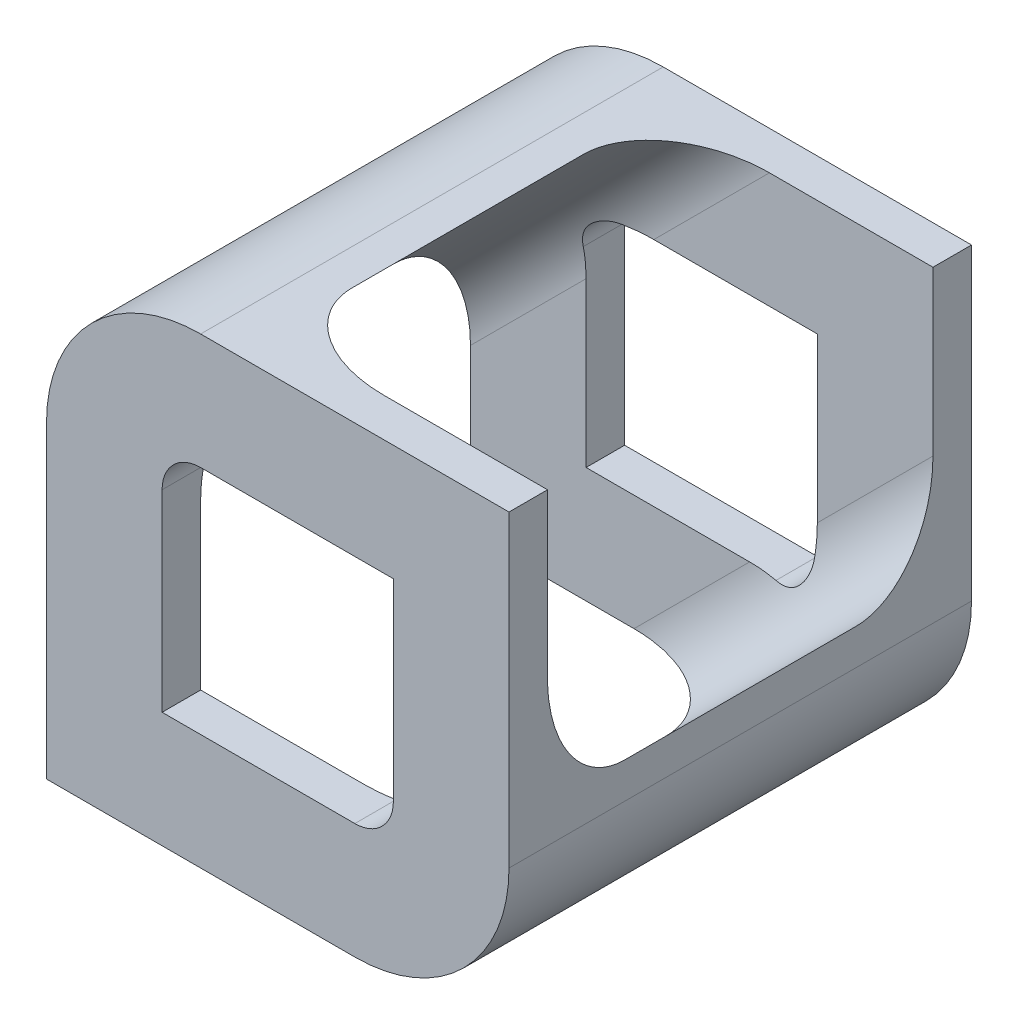
SolidWorks part; units mm, degrees
ref_plane "Front Plane" through (0, 0, 0) normal (0, 0, 1) x (1, 0, 0)
ref_plane "Top Plane" through (0, 0, 0) normal (0, 1, 0) x (1, 0, 0)
ref_plane "Right Plane" through (0, 0, 0) normal (1, 0, 0) x (0, 0, -1)
sketch "Sketch1" plane through (0, 0, 0) normal (0, 0, 1) x (1, 0, 0)
  line L1 (-57.15, -41.275) -> (-6.35, -41.275)
  line L2 (-57.15, -41.275) -> (-57.15, 9.525)
  line L3 (-31.75, 34.925) -> (19.05, 34.925)
  line L4 (19.05, -15.875) -> (19.05, 34.925)
  line L5 (-57.15, -41.275) -> (19.05, 34.925) construction
  line L6 (-57.15, 34.925) -> (19.05, -41.275) construction
  line L7 (-38.1, -22.225) -> (-6.35, -22.225)
  line L8 (-38.1, -22.225) -> (-38.1, 9.525)
  line L9 (-31.75, 15.875) -> (0, 15.875)
  line L10 (0, -15.875) -> (0, 15.875)
  line L11 (-38.1, -22.225) -> (0, 15.875) construction
  line L12 (-38.1, 15.875) -> (0, -22.225) construction
  arc A0 (-6.35, -22.225) -> (0, -15.875) centre (-6.35, -15.875) ccw
  arc A1 (-38.1, 9.525) -> (-31.75, 15.875) centre (-31.75, 9.525) cw
  arc A2 (-6.35, -41.275) -> (19.05, -15.875) centre (-6.35, -15.875) ccw
  arc A3 (-57.15, 9.525) -> (-31.75, 34.925) centre (-31.75, 9.525) cw
  point P0 (0, 0)
  point P1 (0, 0)
  point P6 (0, 0)
  dimension "D6" = 6.35
  dimension "D7" = 25.4
  dimension "D8" = 25.4
  dimension "D1" = 76.2
  dimension "D2" = 76.2
  dimension "D3" = 19.05
  dimension "D4" = 19.05
  dimension "D5" = 19.05
extrude "Boss-Extrude5" add sketch "Sketch1" along normal blind 76.2
ref_plane "Plane1" through (26.9875, 26.9875, 0) normal (0.7071, 0.7071, 0) x (0.7071, -0.7071, 0)
sketch "Sketch5" plane through (26.9875, 26.9875, 0) normal (0.7071, 0.7071, 0) x (0.7071, -0.7071, 0)
  line L0 (-11.2253, -76.2) -> (-11.2253, 0) construction
  line L1 (-30.2753, -69.85) -> (7.8247, -69.85)
  line L2 (-42.9753, -57.15) -> (-42.9753, -19.05)
  line L3 (-30.2753, -6.35) -> (7.8247, -6.35)
  line L4 (20.5247, -57.15) -> (20.5247, -19.05)
  line L5 (-42.9753, -69.85) -> (20.5247, -6.35) construction
  line L6 (-42.9753, -6.35) -> (20.5247, -69.85) construction
  arc A0 (-30.2753, -69.85) -> (-42.9753, -57.15) centre (-30.2753, -57.15) cw
  arc A1 (7.8247, -69.85) -> (20.5247, -57.15) centre (7.8247, -57.15) ccw
  arc A2 (7.8247, -6.35) -> (20.5247, -19.05) centre (7.8247, -19.05) cw
  arc A3 (-42.9753, -19.05) -> (-30.2753, -6.35) centre (-30.2753, -19.05) cw
  point P0 (-11.2253, -38.1)
  dimension "D3" = 12.7
  dimension "D1" = 63.5
  dimension "D2" = 63.5
extrude "Cut-Extrude1" cut sketch "Sketch5" against normal through all
